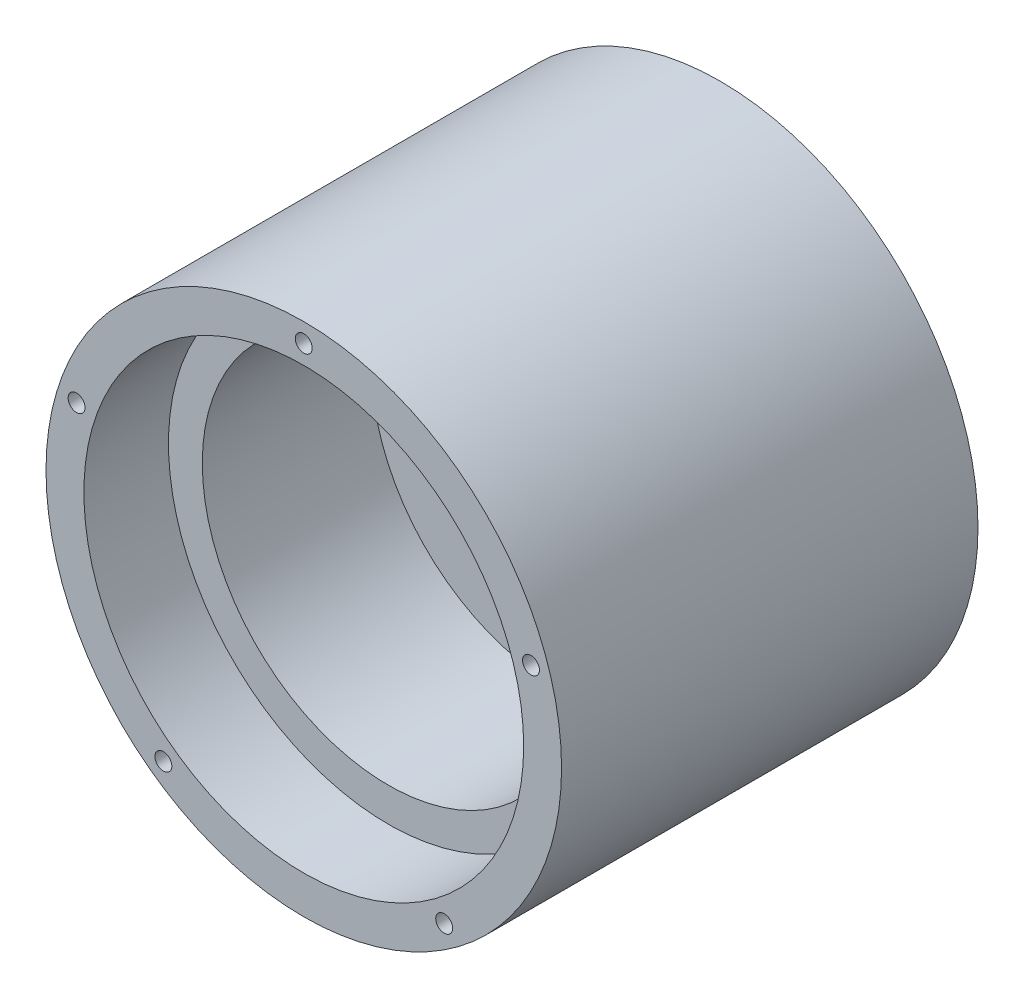
SolidWorks part; units mm, degrees
ref_plane "Front Plane" through (0, 0, 0) normal (1, 0, 0) x (0, 1, 0)
ref_plane "Top Plane" through (0, 0, 0) normal (0, 0, 1) x (0, 1, 0)
ref_plane "Right Plane" through (0, 0, 0) normal (0, 1, 0) x (-1, 0, 0)
sketch "Sketch2" plane through (0, 0, 0) normal (0, 0, 1) x (0, 1, 0)
  circle A0 centre (0, 0) radius 76.2
  dimension "D1" = 152.4
extrude "Boss-Extrude1" add sketch "Sketch2" along normal blind 85 contours A0
sketch "Sketch4" plane through (0, 0, 85) normal (0, 0, 1) x (1, 0, 0)
  circle A0 centre (0, 0) radius 65
  dimension "D1" = 130
extrude "Cut-Extrude2" cut sketch "Sketch4" against normal blind 25
sketch "Sketch5" plane through (0, 0, 60) normal (0, 0, 1) x (1, 0, 0)
  circle A0 centre (0, 0) radius 55
  dimension "D1" = 110
extrude "Cut-Extrude3" cut sketch "Sketch5" against normal blind 50
sketch "Sketch7" plane through (0, 0, 85) normal (0, 0, 1) x (1, 0, 0)
  circle A0 centre (0, 70.612) radius 2.5
  circle A1 centre (0, 0) radius 76.2 construction
  dimension "D1" = 5
  dimension "D2" = 70.612
extrude "Cut-Extrude4" cut sketch "Sketch7" against normal blind 20
pattern_circular "CirPattern1" count 5 over 360 about axis through (0, 0, 0) along (0, 0, 1) of "Cut-Extrude4"
sketch "Sketch8" plane through (0, 0, 0) normal (0, 0, -1) x (1, 0, 0)
  circle A0 centre (0, 0) radius 50.8
  circle A1 centre (0, 0) radius 76.2
  dimension "D1" = 101.6
  dimension "D2" = 152.4
extrude "Boss-Extrude2" add sketch "Sketch8" along normal blind 38.1
sketch "Sketch10" plane through (0, 0, 0) normal (1, 0, 0) x (0, 1, 0)
  line L0 (0, 88.1002) -> (0, -44.7783) construction
  line L1 (0, 10.52) -> (-25.3721, 10)
  line L2 (55, 10) -> (-55, 10) construction
  line L3 (-25.3721, 10) -> (-25.3721, 0)
  line L4 (-50.8, 0) -> (50.8, 0) construction
  line L5 (-25.3721, 0) -> (-63.593, 0)
  line L6 (-63.593, 0) -> (-63.593, -38.1)
  line L7 (-76.2, -38.1) -> (76.2, -38.1) construction
  line L8 (-63.593, -38.1) -> (0, -38.1)
  line L9 (-50.8, -38.1) -> (50.8, -38.1) construction
  line L10 (0, -38.1) -> (0, 10.52)
revolve "Cut-Revolve1" cut sketch "Sketch10" angle 360 about L10
equation "\"o.2\"=0.187569"
